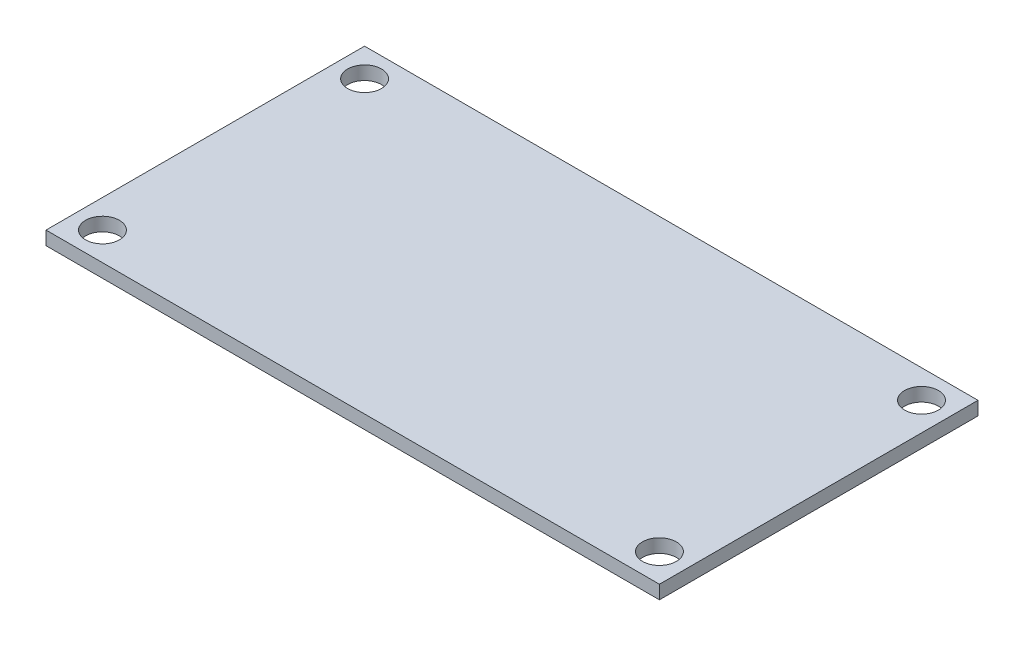
SolidWorks part; units mm, degrees
ref_plane "Alzado" through (0, 0, 0) normal (0, 0, 1) x (1, 0, 0)
ref_plane "Planta" through (0, 0, 0) normal (0, 1, 0) x (1, 0, 0)
ref_plane "Vista lateral" through (0, 0, 0) normal (1, 0, 0) x (0, 0, -1)
sketch "Croquis1" plane through (0, 0, 0) normal (0, 1, 0) x (1, 0, 0)
  line L1 (27.15, 14.1) -> (-27.15, 14.1)
  line L2 (27.15, 14.1) -> (27.15, -14.1)
  line L3 (27.15, -14.1) -> (-27.15, -14.1)
  line L4 (-27.15, 14.1) -> (-27.15, -14.1)
  line L5 (27.15, 14.1) -> (-27.15, -14.1) construction
  line L6 (27.15, -14.1) -> (-27.15, 14.1) construction
  point P0 (0, 0)
  dimension "D1" = 54.3
  dimension "D2" = 28.2
extrude "Saliente-Extruir1" add sketch "Croquis1" along normal blind 1.2
sketch "Croquis3" plane through (0, 1.2, 0) normal (0, 1, 0) x (1, 0, 0)
  line L0 (27.15, 14.1) -> (-27.15, 14.1) construction
  line L1 (-27.15, 14.1) -> (-27.15, -14.1) construction
  line L2 (0, 14.1) -> (0, -14.1) construction
  line L3 (-27.15, -14.1) -> (27.15, -14.1) construction
  line L4 (-27.15, 0) -> (27.15, 0) construction
  line L5 (27.15, -14.1) -> (27.15, 14.1) construction
  circle A0 centre (-24.65, 11.6) radius 1.5
  circle A1 centre (24.65, 11.6) radius 1.5
  circle A2 centre (24.65, -11.6) radius 1.5
  circle A3 centre (-24.65, -11.6) radius 1.5
  dimension "D1" = 3
  dimension "D2" = 2.5
  dimension "D3" = 2.5
extrude "Cortar-Extruir1" cut sketch "Croquis3" against normal blind 1.2
